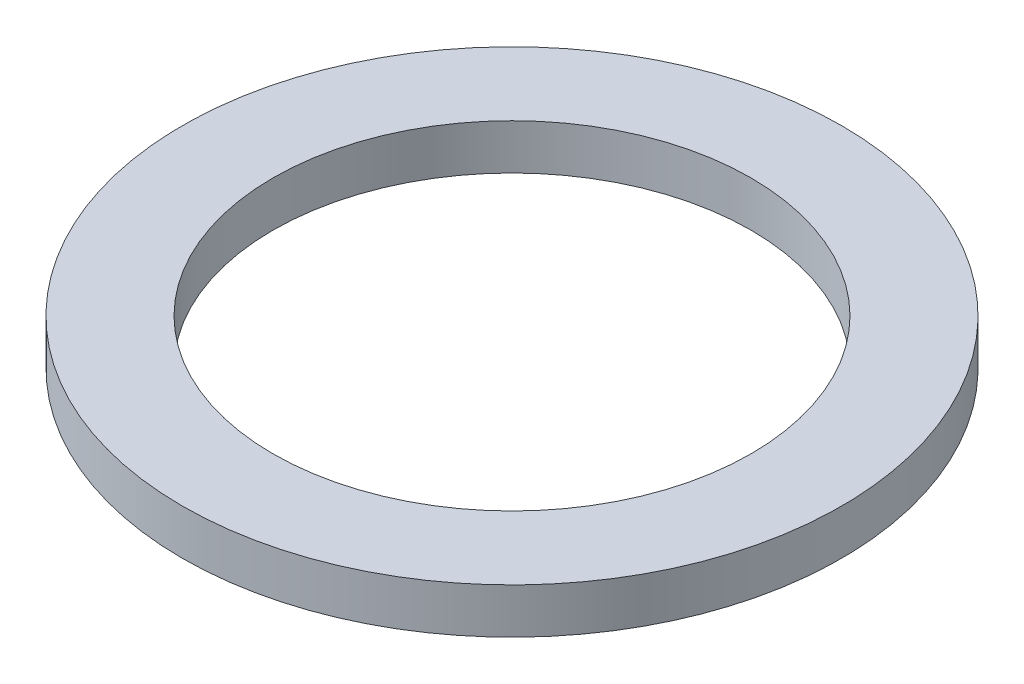
SolidWorks part; units mm, degrees
ref_plane "Front Plane" through (0, 0, 0) normal (0, 0, 1) x (1, 0, 0)
ref_plane "Top Plane" through (0, 0, 0) normal (0, 1, 0) x (1, 0, 0)
ref_plane "Right Plane" through (0, 0, 0) normal (1, 0, 0) x (0, 0, -1)
sketch "Sketch1" plane through (0, 0, 0) normal (1, 0, 0) x (0, 0, -1)
  line L0 (26.0878, 274.978) -> (26.0878, 232.1195) construction
  line L2 (40.135, 302.9291) -> (40.135, 295.6281) construction
  line L5 (0, 324) -> (3.2968, 324) construction
  line L7 (21.6442, 186.0993) -> (0, 186.0993) construction
  line L9 (26.0878, 262.3641) -> (26.0878, 259.4973) construction
  line L16 (0, 0) -> (51.9362, 327.9125) construction
  line L17 (0, 324) -> (0, 332) construction
  line L18 (26.0878, 274.978) -> (26.0878, 268.978) construction
  line L19 (26.0878, 268.978) -> (26.0878, 248.978) construction
  line L20 (26.0878, 268.978) -> (42.6019, 268.978) construction
  line L21 (26.0878, 274.978) -> (43.5522, 274.978) construction
  line L22 (26.0878, 248.978) -> (39.4342, 248.978) construction
  line L23 (0, 0) -> (-51.9362, 327.9125) construction
  line L24 (-47.4003, 299.274) -> (-47.4003, 268.978) construction
  line L25 (-47.4003, 268.978) -> (-42.6019, 268.978) construction
  line L26 (40.135, 295.6281) -> (40.435, 295.6281) construction
  line L27 (0, 76.96) -> (400, 76.96) construction
  line L28 (0, 76.96) -> (-400, 76.96) construction
  line L29 (-200, 76.96) -> (-200, 183.96) construction
  line L30 (200, 76.96) -> (200, 183.96) construction
  line L31 (-200, 183.96) -> (-200, 182.57) construction
  line L32 (-200, 182.57) -> (400, 182.57) construction
  line L33 (-200, 182.57) -> (-400, 182.57) construction
  line L36 (21.6442, 186.0993) -> (21.6442, 226.0993) construction
  line L37 (0, 324) -> (0, 186.1152) construction
  line L38 (0, 186.1152) -> (0, 186.0993)
  line L39 (0, 0) -> (-2, 0) construction
  line L40 (-2, 0) -> (49.9843, 328.2157) construction
  line L41 (51.9362, 327.9125) -> (49.9362, 327.9125) construction
  line L42 (26.0878, 274.978) -> (26.3878, 274.978) construction
  line L43 (26.0878, 274.978) -> (26.0878, 273.978) construction
  line L44 (26.2311, 276.2681) -> (26.5311, 276.2681) construction
  line L45 (26.6611, 277.4147) -> (26.9611, 277.4147) construction
  line L46 (27.2344, 278.5614) -> (27.5344, 278.5614) construction
  line L47 (27.9512, 279.4215) -> (28.2512, 279.4215) construction
  line L48 (28.9545, 280.5682) -> (29.2545, 280.5682) construction
  line L49 (29.8146, 281.4282) -> (30.1146, 281.4282) construction
  line L50 (30.8179, 282.4316) -> (31.1179, 282.4316) construction
  line L51 (31.8213, 283.2917) -> (32.1213, 283.2917) construction
  line L52 (32.8246, 284.2951) -> (33.1246, 284.2951) construction
  line L53 (33.8281, 285.2984) -> (34.1281, 285.2984) construction
  line L54 (34.9748, 286.3018) -> (35.2748, 286.3018) construction
  line L55 (35.9781, 287.3051) -> (36.2781, 287.3051) construction
  line L56 (36.8382, 288.1652) -> (37.1382, 288.1652) construction
  line L57 (37.8416, 289.3119) -> (38.1416, 289.3119) construction
  line L58 (38.5582, 290.4586) -> (38.8582, 290.4586) construction
  line L59 (39.1315, 291.7487) -> (39.4315, 291.7487) construction
  line L60 (39.5617, 292.8954) -> (39.8617, 292.8954) construction
  line L61 (39.8483, 294.0421) -> (40.1483, 294.0421) construction
  line L63 (40.135, 302.9291) -> (40.435, 302.9291) construction
  line L64 (26.0878, 273.978) -> (26.3878, 273.978) construction
  line L68 (0, 332) -> (36.0261, 332) construction
  line L69 (36.0261, 332) -> (36.0261, 309.4264) construction
  line L70 (36.0261, 309.4264) -> (48.951, 321.6917) construction
  line L71 (36.0261, 309.4264) -> (49.0083, 309.4264) construction
  line L73 (36.0261, 309.4264) -> (46.0928, 318.9794) construction
  line L74 (46.0928, 318.9794) -> (46.0928, 386.8005) construction
  line L75 (46.0928, 318.9794) -> (19.4833, 320.3739) construction
  line L76 (19.4833, 320.3739) -> (20.8454, 323.7133) construction
  line L77 (19.4833, 320.3739) -> (28.7426, 316.597) construction
  line L78 (19.4833, 320.3739) -> (10.2239, 324.1508) construction
  line L79 (10.2239, 324.1508) -> (9.7753, 323.0511) construction
  line L80 (28.7426, 316.597) -> (28.4187, 315.803) construction
  arc A0 (-298.7691, 144.7791) -> (305.6579, 129.6043) centre (0, 0) cw construction
  spline S0 degree 3 poles (21.6442, 226.0993) (22.3362, 225.9573) (23.1249, 226.5484) (24.2443, 227.206) (25.0066, 227.971) (25.5796, 228.9526) (25.8622, 230.3928) (26.0228, 231.4438) (26.0878, 232.1195) knots 0 0 0 0 0.223849 0.348959 0.47164 0.61152 0.754586 1 1 1 1 construction
  spline S1 degree 3 poles (3.2968, 324) (4.1972, 323.8396) (5.699, 323.816) (7.6935, 323.4297) (9.2722, 323.1563) (10.7507, 322.8538) (12.1816, 322.5577) (13.6372, 322.313) (14.8643, 321.9117) (15.9115, 321.5662) (16.81, 321.2491) (17.7339, 321.0149) (18.8379, 320.6416) (19.931, 320.1935) (21.0686, 319.6948) (22.141, 319.2627) (23.2156, 318.6856) (24.4371, 318.1163) (25.6762, 317.3518) (27.1066, 316.7518) (28.4318, 315.7832) (29.7322, 314.8939) (31.058, 313.93) (32.1959, 312.8581) (33.3378, 311.8503) (34.4539, 310.9646) (35.3895, 309.8867) (36.5078, 309.0949) (37.2942, 308.0208) (38.1233, 307.1238) (38.9048, 306.0961) (39.4724, 304.6349) (40.2774, 303.734) (40.135, 302.9291) knots 0 0 0 0 0.061585 0.100795 0.136831 0.1697 0.202569 0.235438 0.269088 0.289473 0.309858 0.333319 0.353706 0.388423 0.412965 0.437514 0.46634 0.495168 0.528354 0.564387 0.59925 0.638593 0.670824 0.709635 0.743897 0.773612 0.805519 0.839783 0.864953 0.89467 0.922395 0.951224 1 1 1 1 construction
  spline S2 degree 3 poles (40.135, 295.6188) (39.9636, 294.7131) (39.7869, 293.3689) (39.1095, 291.6901) (38.6019, 290.4599) (37.8418, 289.2392) (36.9195, 288.2279) (35.9232, 287.2651) (34.974, 286.2515) (33.8311, 285.3463) (32.8233, 284.2966) (31.8701, 283.2868) (30.7668, 282.4387) (29.8742, 281.4644) (28.8604, 280.5152) (28.0567, 279.5119) (27.1438, 278.5569) (26.4968, 277.0287) (26.0081, 275.8567) (26.0878, 274.978) knots 0 0 0 0 0.108356 0.15601 0.210945 0.263562 0.322855 0.370186 0.425399 0.484692 0.539909 0.595126 0.646549 0.701764 0.749093 0.808384 0.85195 0.901837 1 1 1 1 construction
  dimension "D2" = 2
  dimension "D4" = 8
  dimension "D5" = 2
  dimension "D6" = 36.0261
  dimension "D8" = 70.809
  dimension "D9" = 6
  dimension "D10" = 20
  dimension "D11" = 1.1877
  dimension "D12" = 0.8575
  dimension "D13" = 255.04
  dimension "D14" = 107
  dimension "D15" = 107
  dimension "D16" = 332
  dimension "D17" = 105.61
  dimension "D18" = 105.61
  dimension "D19" = 40
  dimension "D20" = 90
  dimension "D21" = 46.5
sketch "poron" plane through (0, 0, 0) normal (1, 0, 0) x (0, 0, -1)
  line L0 (0, 0) -> (0, 354.6797) construction
  line L9 (26.3878, 268.978) -> (36.3857, 268.978)
  line L10 (26.0878, 268.978) -> (42.6019, 268.978) construction
  line L11 (36.3857, 268.978) -> (36.3857, 273.978)
  line L12 (26.3878, 268.978) -> (26.3878, 273.978)
  line L13 (26.3878, 273.978) -> (36.3857, 273.978)
revolve "Revolve1" add sketch "poron" angle 360 about L0
